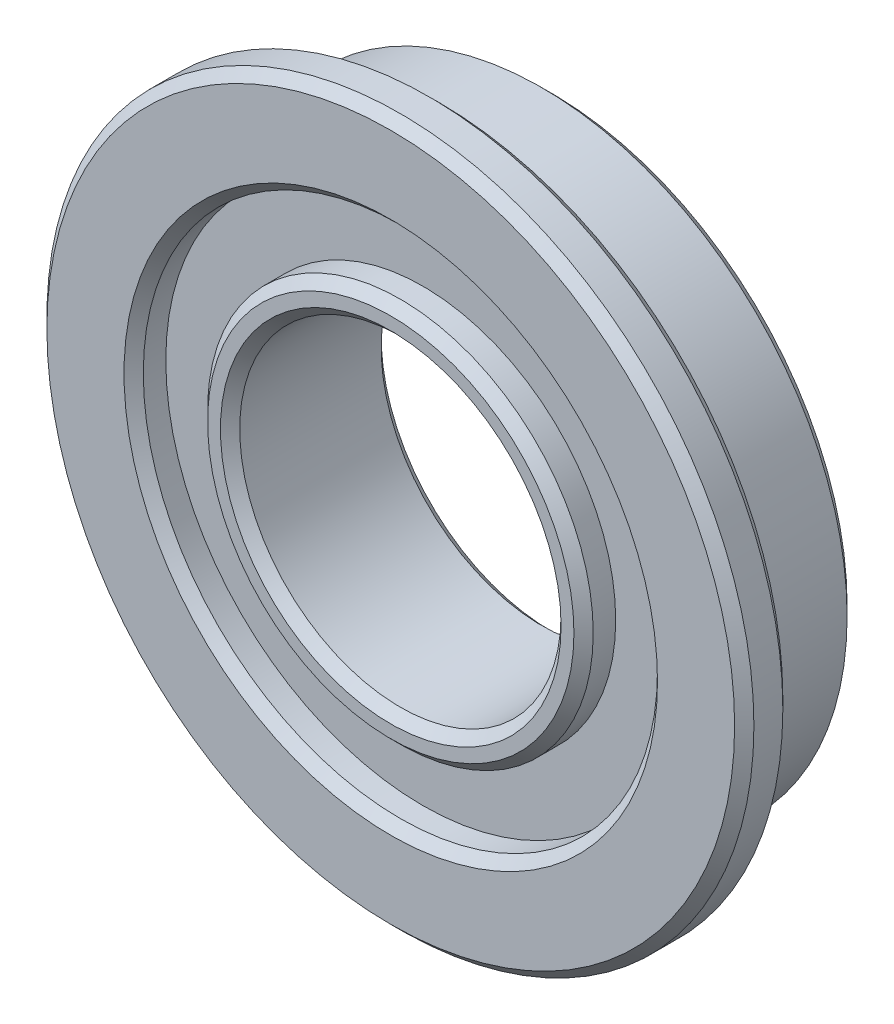
SolidWorks part; units mm, degrees
ref_plane "Спереди" through (0, 0, 0) normal (0, 0, 1) x (1, 0, 0)
ref_plane "Сверху" through (0, 0, 0) normal (0, 1, 0) x (1, 0, 0)
ref_plane "Справа" through (0, 0, 0) normal (1, 0, 0) x (0, 0, -1)
other "Configuration Table"
sketch "Эскиз1" plane through (0, 0, 0) normal (0, 0, 1) x (1, 0, 0)
  circle A0 centre (0, 0) radius 9.5
  circle A1 centre (0, 0) radius 5
  dimension "D1" = 19
  dimension "D2" = 10
extrude "Бобышка-Вытянуть1" add sketch "Эскиз1" along normal blind 5
sketch "Эскиз2" plane through (0, 0, 5) normal (0, 0, 1) x (1, 0, 0)
  circle A0 centre (0, 0) radius 11
  circle A1 centre (0, 0) radius 9.5
  dimension "D1" = 22
extrude "Бобышка-Вытянуть2" add sketch "Эскиз2" against normal blind 1.5
sketch "Эскиз3" plane through (0, 0, 0) normal (0, 0, -1) x (-1, 0, 0)
  circle A0 centre (0, 0) radius 6
  circle A1 centre (0, 0) radius 8
  dimension "D1" = 16
  dimension "D2" = 12
extrude "Вырез-Вытянуть1" cut sketch "Эскиз3" against normal blind 1
sketch "Эскиз4" plane through (0, 0, 5) normal (0, 0, 1) x (1, 0, 0)
  circle A0 centre (0, 0) radius 6
  circle A1 centre (0, 0) radius 8
  dimension "D1" = 16
  dimension "D2" = 12
extrude "Вырез-Вытянуть2" cut sketch "Эскиз4" against normal blind 1
chamfer "Фаска1" distance 0.3 angle 45 9 edges at (11, 0, 3.5) (11, 0, 5) (-8, 0, 0) (-6, 0, 0) (9.5, 0, 0) (8, 0, 5) (6, 0, 5) (5, 0, 0) (5, 0, 5)
